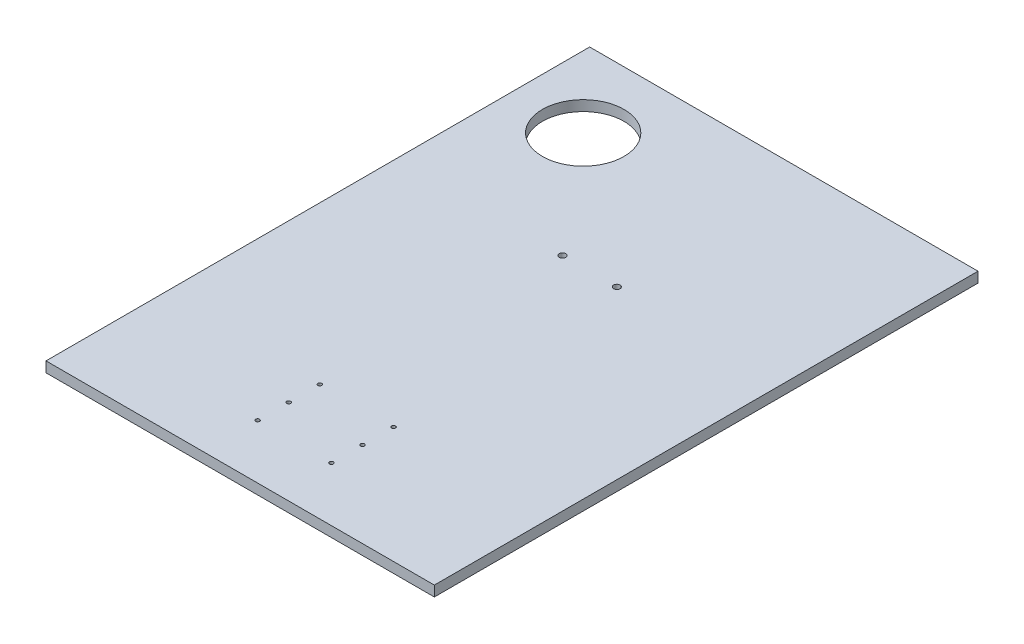
SolidWorks part; units mm, degrees
ref_plane "Front Plane" through (0, 0, 0) normal (0, 0, 1) x (1, 0, 0)
ref_plane "Top Plane" through (0, 0, 0) normal (0, 1, 0) x (1, 0, 0)
ref_plane "Right Plane" through (0, 0, 0) normal (1, 0, 0) x (0, 0, -1)
sketch "Sketch1" plane through (0, 0, 0) normal (0, 1, 0) x (1, 0, 0)
  line L0 (0, 210) -> (0, -210) construction
  line L1 (-150, -210) -> (150, -210)
  line L2 (-150, -210) -> (-150, 210)
  line L3 (-150, 210) -> (150, 210)
  line L4 (150, -210) -> (150, 210)
  line L5 (-150, -210) -> (150, 210) construction
  line L6 (-150, 210) -> (150, -210) construction
  line L7 (-28.5, -120) -> (-28.5, -144) construction
  line L8 (-28.5, -144) -> (-28.5, -168) construction
  circle A8 centre (-21, 60) radius 2.5
  circle A9 centre (21, 60) radius 2.5
  circle A10 centre (-28.5, -120) radius 1.5
  circle A11 centre (-28.5, -144) radius 1.5
  circle A12 centre (-28.5, -168) radius 1.5
  circle A13 centre (28.5, -168) radius 1.5
  circle A14 centre (28.5, -144) radius 1.5
  circle A15 centre (28.5, -120) radius 1.5
  circle A16 centre (-95, 150) radius 31.5
  point P0 (0, 0)
  dimension "D4" = 3
  dimension "D5" = 28.5
  dimension "D6" = 90
  dimension "D8" = 5
  dimension "D9" = 21
  dimension "D10" = 150
  dimension "D7" = 63
  dimension "D1" = 300
  dimension "D2" = 420
  dimension "D3" = 24
extrude "Boss-Extrude1" add sketch "Sketch1" along normal blind 8
